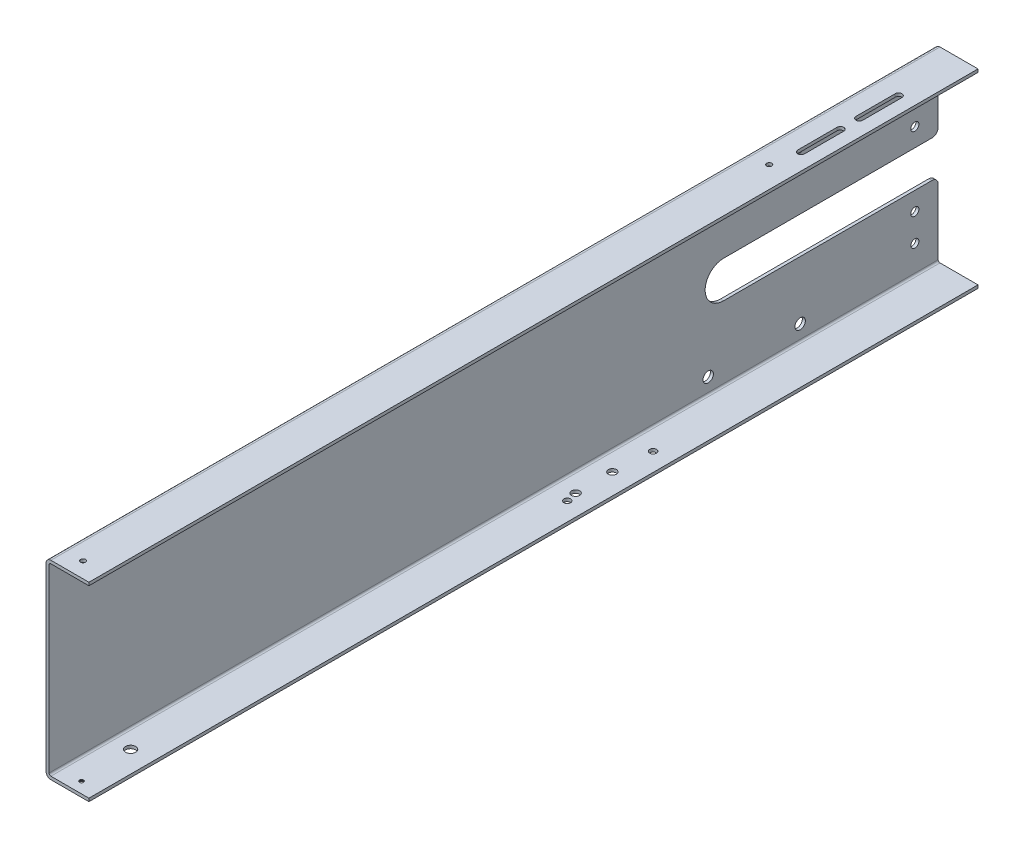
SolidWorks part; units mm, degrees
material "AISI 304"
ref_plane "Спереди" through (0, 0, 0) normal (0, 0, 1) x (1, 0, 0)
ref_plane "Сверху" through (0, 0, 0) normal (0, 1, 0) x (1, 0, 0)
ref_plane "Справа" through (0, 0, 0) normal (1, 0, 0) x (0, 0, -1)
sketch "Эскиз1" plane through (0, 0, 0) normal (0, 0, 1) x (1, 0, 0)
  line L0 (70, 0) -> (8, 0)
  line L1 (0, 8) -> (0, 302)
  line L2 (8, 310) -> (70, 310)
  line L8 (70, 5) -> (8, 5)
  line L9 (5, 8) -> (5, 302)
  line L10 (8, 305) -> (70, 305)
  line L11 (70, 310) -> (70, 305)
  line L12 (70, 5) -> (70, 0)
  arc A0 (0, 302) -> (8, 310) centre (8, 302) cw
  arc A1 (8, 0) -> (0, 8) centre (8, 8) cw
  arc A2 (8, 5) -> (5, 8) centre (8, 8) cw
  arc A3 (5, 302) -> (8, 305) centre (8, 302) cw
  point P9 (0, 0)
  dimension "D2" = 8
  dimension "D3" = 310
  dimension "D1" = 70
  dimension "D4" = 5
extrude "Бобышка-Вытянуть1" add sketch "Эскиз1" along normal blind 1450
sketch "Эскиз2" plane through (0, 0, 0) normal (-1, 0, 0) x (0, 0, 1)
  line L0 (350, 155) -> (0, 155) construction
  line L2 (0, 302) -> (0, 8) construction
  line L3 (350, 125) -> (0, 125)
  line L4 (350, 185) -> (0, 185)
  line L5 (0, 185) -> (0, 125)
  line L6 (0, 8) -> (0, 302) construction
  arc A0 (350, 125) -> (350, 185) centre (350, 155) ccw
  dimension "D1" = 60
  dimension "D2" = 350
extrude "Прорезь для опоры" cut sketch "Эскиз2" against normal blind 10
sketch "Эскиз3" plane through (5, 0, 0) normal (1, 0, 0) x (0, 0, -1)
  line L2 (-380, 155) -> (109.9604, 155) construction
  line L3 (-300, 155) -> (-300, 228.5) construction
  line L18 (0, 302) -> (0, 185) construction
  arc A0 (-350, 185) -> (-350, 125) centre (-350, 155) ccw construction
  circle A16 centre (-225, 280) radius 8.5
  circle A27 centre (-225, 30) radius 8.5
  circle A28 centre (-375, 280) radius 8.5
  circle A29 centre (-375, 30) radius 8.5
  dimension "D1" = 125
  dimension "D2" = 250
  dimension "D7" = 17
  dimension "D5" = 300
  dimension "D6" = 75
extrude "Отверстия опоры" cut sketch "Эскиз3" against normal mid plane 10
sketch "Эскиз9" plane through (0, 0, 0) normal (-1, 0, 0) x (0, 0, 1)
  line L0 (980, 260) -> (740, 260) construction
  line L1 (778, 240) -> (942, 240)
  line L2 (760, 258) -> (760, 262)
  line L3 (778, 280) -> (942, 280)
  line L4 (960, 258) -> (960, 262)
  line L5 (760, 240) -> (960, 280) construction
  line L6 (760, 280) -> (960, 240) construction
  line L7 (0, 302) -> (0, 185) construction
  line L8 (1450, 310) -> (0, 310) construction
  arc A0 (942, 240) -> (960, 258) centre (942, 258) ccw
  arc A1 (942, 280) -> (960, 262) centre (942, 262) cw
  arc A2 (760, 262) -> (778, 280) centre (778, 262) cw
  arc A3 (778, 240) -> (760, 258) centre (778, 258) cw
  circle A4 centre (740, 260) radius 4
  circle A5 centre (980, 260) radius 4
  point P0 (860, 260)
  point P24 (860, 260)
  dimension "D5" = 18
  dimension "D6" = 8
  dimension "D1" = 40
  dimension "D2" = 200
  dimension "D3" = 50
  dimension "D4" = 760
  dimension "D7" = 240
extrude "Окно для цепочки" cut sketch "Эскиз9" against normal blind 10
sketch "Эскиз12" plane through (0, 0, 0) normal (-1, 0, 0) x (0, 0, 1)
  line L0 (0, 185) -> (0, 125) construction
  line L1 (0, 302) -> (0, 185) construction
  line L2 (38, 215) -> (38, 260) construction
  line L3 (0, 155) -> (47.6879, 155) construction
  circle A0 centre (38, 215) radius 6.6
  circle A1 centre (38, 260) radius 6.6
  circle A5 centre (38, 95) radius 6.6
  circle A6 centre (38, 50) radius 6.6
  dimension "D2" = 45
  dimension "D3" = 38
  dimension "D4" = 13.2
  dimension "D1" = 60
extrude "Отверстия для натяжителя" cut sketch "Эскиз12" against normal blind 10
sketch "Эскиз13" plane through (0, 310, 0) normal (0, 1, 0) x (1, 0, 0)
  line L0 (43, 0) -> (43, -182) construction
  line L1 (70, 0) -> (8, 0) construction
  line L2 (43, -182) -> (70, -182) construction
  line L3 (70, -1450) -> (70, 0) construction
  line L4 (43, -166.5) -> (43, -102.5) construction
  line L5 (37.5, -166.5) -> (37.5, -102.5)
  line L6 (48.5, -166.5) -> (48.5, -102.5)
  line L7 (43, -261.5) -> (43, -197.5) construction
  line L8 (37.5, -261.5) -> (37.5, -197.5)
  line L9 (48.5, -261.5) -> (48.5, -197.5)
  line L10 (43, -137) -> (43, -132) construction
  line L11 (36.5, -137) -> (36.5, -132) construction
  line L12 (49.5, -137) -> (49.5, -132) construction
  line L13 (75.7473, -259.5) -> (97.0198, -259.5) construction
  circle A0 centre (43, -134.5) radius 5.5 construction
  circle A1 centre (43, -229.5) radius 5.5 construction
  arc A2 (37.5, -166.5) -> (48.5, -166.5) centre (43, -166.5) ccw
  arc A3 (48.5, -102.5) -> (37.5, -102.5) centre (43, -102.5) ccw
  arc A4 (37.5, -261.5) -> (48.5, -261.5) centre (43, -261.5) ccw
  arc A5 (48.5, -197.5) -> (37.5, -197.5) centre (43, -197.5) ccw
  arc A6 (36.5, -137) -> (49.5, -137) centre (43, -137) ccw construction
  arc A7 (49.5, -132) -> (36.5, -132) centre (43, -132) ccw construction
  point P13 (43, -134.5)
  point P19 (43, -229.5)
  point P27 (43, -134.5)
  dimension "D2" = 95
  dimension "D3" = 11
  dimension "D5" = 75
  dimension "D6" = 18
  dimension "D1" = 182
  dimension "D4" = 27
  dimension "D7" = 13
extrude "Установка подшипников" cut sketch "Эскиз13" against normal blind 10
sketch "Эскиз17" plane through (0, 0, 0) normal (0, -1, 0) x (-1, 0, 0)
  line L0 (-36, -562.3) -> (-36, -622.3) construction
  line L1 (-70, -1450) -> (-70, 0) construction
  line L2 (-8, 0) -> (-70, 0) construction
  circle A0 centre (-36, -562.3) radius 6.6
  circle A1 centre (-36, -622.3) radius 6.6
  dimension "D1" = 13.2
  dimension "D4" = 562.3
  dimension "D2" = 60
  dimension "D3" = 34
extrude "Отверстия крепления сброса" cut sketch "Эскиз17" against normal blind 10
fillet "Скругление1" radius 10 2 edges at (2.5, 185, 0) (2.5, 125, 0)
sketch "Эскиз21" plane through (0, 310, 0) normal (0, 1, 0) x (1, 0, 0)
  line L1 (35, -898.5) -> (35, -305.5) construction
  line L2 (-3.5, -940.5) -> (-3.5, -535.5) construction
  circle A0 centre (35, -898.5) radius 4.1 construction
  circle A1 centre (35, -305.5) radius 4.1
  circle A3 centre (35, -1063) radius 4.1 construction
  dimension "D1" = 8.2
  dimension "D3" = 593
  dimension "D2" = 305.5
  dimension "D5" = 164.5
  dimension "D4" = 38.5
extrude "Отверстия крепления крышки 1" cut sketch "Эскиз21" against normal up to surface (5 mm away) up to face at (43, 305, 134.5)
sketch "Эскиз22" plane through (0, 0, 0) normal (0, -1, 0) x (1, 0, 0)
  line L0 (40.0885, 500) -> (40.0885, 640) construction
  line L1 (70, 1450) -> (70, 0) construction
  line L2 (0, 0) -> (8, 0) construction
  circle A0 centre (40.0885, 500) radius 5.5
  circle A1 centre (40.0885, 640) radius 5.5
  dimension "D2" = 29.9115
  dimension "D3" = 500
  dimension "D4" = 11
  dimension "D1" = 140
extrude "Отверстия крепления обвода" cut sketch "Эскиз22" against normal up to surface (5 mm away) up to face at (42.6, 5, 562.3)
sketch "Эскиз23" plane through (0, 0, 0) normal (0, -1, 0) x (1, 0, 0)
  line L0 (8, 1450) -> (70, 1450) construction
  line L1 (70, 1450) -> (70, 0) construction
  circle A0 centre (35, 1347) radius 8.25
  dimension "D1" = 16.5
  dimension "D2" = 103
  dimension "D3" = 35
extrude "Отверстие шпильки натяжителя" cut sketch "Эскиз23" against normal blind 10
sketch "Эскиз24" plane through (0, 310, 0) normal (0, 1, 0) x (1, 0, 0)
  line L0 (70, -1450) -> (70, 0) construction
  line L1 (70, -1450) -> (8, -1450) construction
  circle A0 centre (35, -1424.5) radius 4.1
  dimension "D1" = 8.2
  dimension "D2" = 35
  dimension "D3" = 25.5
extrude "Отверстие крепления крышки 2" cut sketch "Эскиз24" against normal blind 10
sketch "Эскиз25" plane through (0, 0, 0) normal (0, -1, 0) x (1, 0, 0)
  line L0 (70, 1450) -> (70, 0) construction
  line L1 (8, 1450) -> (70, 1450) construction
  point P0 (40, 1432)
  dimension "D1" = 30
  dimension "D2" = 18
hole_wizard "Зенковка для винта с потайной головкой и внутренним шестигранником M61" positions "Эскиз25" profile "Эскиз26" countersink size "M6" standard "DIN"
sketch "Эскиз26" plane through (40, 0, 1432) normal (1, 0, 0) x (0, 0, -1)
  line L0 (0, 0) -> (0, 11.9828)
  line L1 (0, 11.9828) -> (3.3, 10)
  line L2 (3.3, 10) -> (3.3, 3.555)
  line L3 (3.3, 3.555) -> (6.855, 0)
  line L5 (6.855, 0) -> (0, 0)
  line L6 (-3.3, 3.555) -> (-6.855, 0) construction
  line L10 (0, 11.9828) -> (-3.3, 10) construction
  line L11 (0, -6.35) -> (0, 107.95) construction
  dimension "Диаметр отверстия" = 6.6
  dimension "Глубина отверстия" = 10
  dimension "Диаметр передней зенковки" = 13.71
  dimension "Угол передней зенковки" = 90
  dimension "Угол заточки сверла" = 118
